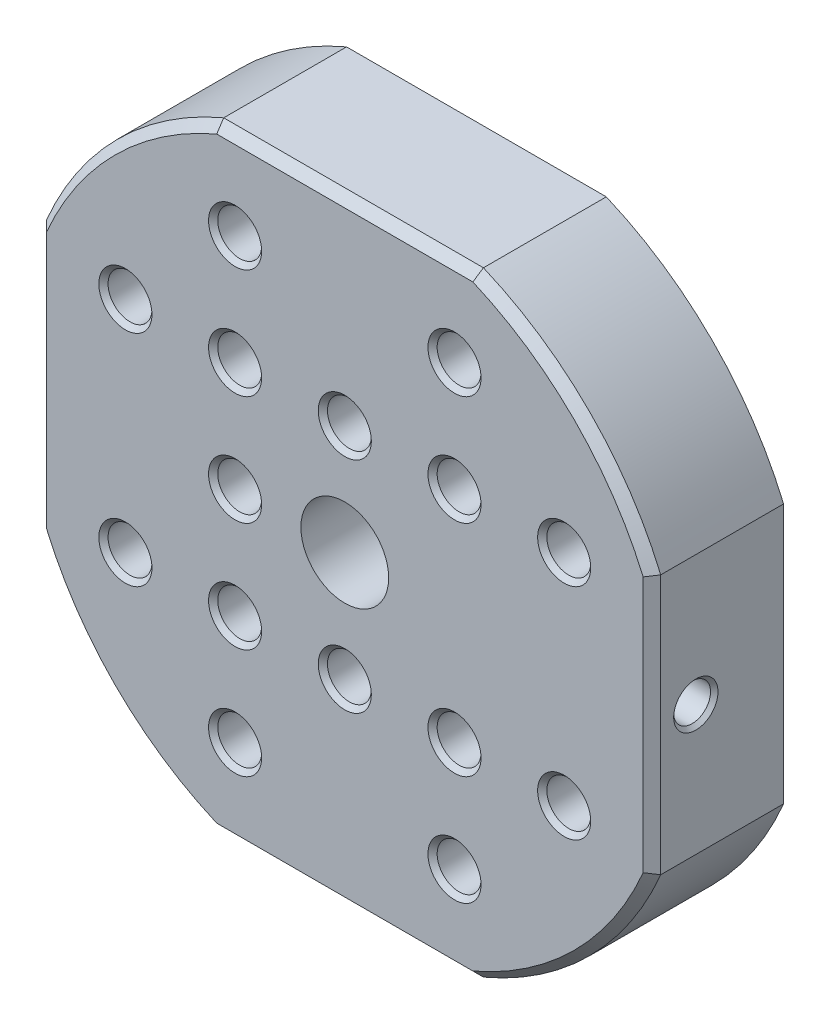
SolidWorks part; units mm, degrees
material "3.3547 (EN-AW 5083)"
ref_plane "Ebene vorne" through (0, 0, 0) normal (0, 0, 1) x (1, 0, 0)
ref_plane "Ebene oben" through (0, 0, 0) normal (0, 1, 0) x (1, 0, 0)
ref_plane "Ebene rechts" through (0, 0, 0) normal (1, 0, 0) x (0, 0, -1)
sketch "Skizze1" plane through (0, 0, 0) normal (0, 0, 1) x (1, 0, 0)
  line L1 (-36.9105, 30.5035) -> (29.0895, 30.5035)
  line L2 (-38.9105, 28.5035) -> (-38.9105, -37.4965)
  line L3 (-36.9105, -39.4965) -> (29.0895, -39.4965)
  line L4 (31.0895, 28.5035) -> (31.0895, -37.4965)
  arc A0 (-38.9105, -37.4965) -> (-36.9105, -39.4965) centre (-36.9105, -37.4965) ccw
  arc A1 (29.0895, -39.4965) -> (31.0895, -37.4965) centre (29.0895, -37.4965) ccw
  arc A2 (29.0895, 30.5035) -> (31.0895, 28.5035) centre (29.0895, 28.5035) cw
  arc A3 (-36.9105, 30.5035) -> (-38.9105, 28.5035) centre (-36.9105, 28.5035) ccw
  circle A4 centre (-3.9105, -4.4965) radius 5
  point P6 (-38.9105, -39.4965)
  point P11 (31.0895, 30.5035)
  point P14 (-38.9105, 30.5035)
  dimension "D3" = 2
  dimension "D1" = 70
  dimension "D2" = 70
extrude "Aufsatz-Linear austragen1" add sketch "Skizze1" along normal blind 15
sketch "Skizze4" plane through (0, 0, 0) normal (0, 0, -1) x (-1, 0, 0)
  circle A0 centre (3.9105, -4.4965) radius 24.75
extrude "Aufsatz-Linear austragen2" add sketch "Skizze4" along normal blind 3
sketch "Skizze2" plane through (0, 0, 15) normal (0, 0, 1) x (1, 0, 0)
  circle A1 centre (-16.4105, 20.5035) radius 2.5
  circle A3 centre (8.5895, 20.5035) radius 2.5
  circle A5 centre (-16.4105, 8.0035) radius 2.5
  circle A6 centre (-3.9105, 8.0035) radius 2.5
  circle A7 centre (8.5895, 8.0035) radius 2.5
  circle A8 centre (21.0895, 8.0035) radius 2.5
  circle A9 centre (-16.4105, -4.4965) radius 2.5
  circle A13 centre (-16.4105, -16.9965) radius 2.5
  circle A14 centre (-3.9105, -16.9965) radius 2.5
  circle A15 centre (8.5895, -16.9965) radius 2.5
  circle A16 centre (21.0895, -16.9965) radius 2.5
  circle A17 centre (-16.4105, -29.4965) radius 2.5
  circle A19 centre (8.5895, -29.4965) radius 2.5
  circle A21 centre (-28.9105, 8.0035) radius 2.5
  circle A23 centre (-28.9105, -16.9965) radius 2.5
extrude "Schnitt-Linear austragen1" cut sketch "Skizze2" against normal blind 20
cosmetic thread "Bohrungsgewinde1" parameters "D1"=13.95, "D2"=6
cosmetic thread "Bohrungsgewinde4" parameters "D1"=13.95, "D2"=6
cosmetic thread "Bohrungsgewinde6" parameters "D1"=13.95, "D2"=6
cosmetic thread "Bohrungsgewinde8" parameters "D1"=13.95, "D2"=6
cosmetic thread "Bohrungsgewinde9" parameters "D1"=13.95, "D2"=6
cosmetic thread "Bohrungsgewinde10" parameters "D1"=13.95, "D2"=6
cosmetic thread "Bohrungsgewinde11" parameters "D1"=13.95, "D2"=6
cosmetic thread "Bohrungsgewinde12" parameters "D1"=13.95, "D2"=6
cosmetic thread "Bohrungsgewinde15" parameters "D1"=13.95, "D2"=6
cosmetic thread "Bohrungsgewinde17" parameters "D1"=13.95, "D2"=6
cosmetic thread "Bohrungsgewinde18" parameters "D1"=13.95, "D2"=6
cosmetic thread "Bohrungsgewinde19" parameters "D1"=13.95, "D2"=6
cosmetic thread "Bohrungsgewinde20" parameters "D1"=13.95, "D2"=6
cosmetic thread "Bohrungsgewinde21" parameters "D1"=13.95, "D2"=6
cosmetic thread "Bohrungsgewinde23" parameters "D1"=13.95, "D2"=6
cosmetic thread "Bohrungsgewinde25" parameters "D1"=13.95, "D2"=6
cosmetic thread "Bohrungsgewinde28" parameters "D1"=13.95, "D2"=6
cosmetic thread "Bohrungsgewinde30" parameters "D1"=13.95, "D2"=6
cosmetic thread "Bohrungsgewinde32" parameters "D1"=13.95, "D2"=6
cosmetic thread "Bohrungsgewinde33" parameters "D1"=13.95, "D2"=6
cosmetic thread "Bohrungsgewinde34" parameters "D1"=13.95, "D2"=6
cosmetic thread "Bohrungsgewinde35" parameters "D1"=13.95, "D2"=6
cosmetic thread "Bohrungsgewinde36" parameters "D1"=13.95, "D2"=6
cosmetic thread "Bohrungsgewinde39" parameters "D1"=13.95, "D2"=6
cosmetic thread "Bohrungsgewinde41" parameters "D1"=13.95, "D2"=6
cosmetic thread "Bohrungsgewinde42" parameters "D1"=13.95, "D2"=6
cosmetic thread "Bohrungsgewinde43" parameters "D1"=13.95, "D2"=6
cosmetic thread "Bohrungsgewinde44" parameters "D1"=13.95, "D2"=6
cosmetic thread "Bohrungsgewinde45" parameters "D1"=13.95, "D2"=6
cosmetic thread "Bohrungsgewinde47" parameters "D1"=13.95, "D2"=6
cosmetic thread "Bohrungsgewinde49" parameters "D1"=13.95, "D2"=6
cosmetic thread "Bohrungsgewinde52" parameters "D1"=12.475, "D2"=6
cosmetic thread "Bohrungsgewinde54" parameters "D1"=12.475, "D2"=6
cosmetic thread "Bohrungsgewinde56" parameters "D1"=12.475, "D2"=6
cosmetic thread "Bohrungsgewinde57" parameters "D1"=12.475, "D2"=6
cosmetic thread "Bohrungsgewinde58" parameters "D1"=12.475, "D2"=6
cosmetic thread "Bohrungsgewinde59" parameters "D1"=12.475, "D2"=6
cosmetic thread "Bohrungsgewinde60" parameters "D1"=12.475, "D2"=6
cosmetic thread "Bohrungsgewinde63" parameters "D1"=12.475, "D2"=6
cosmetic thread "Bohrungsgewinde65" parameters "D1"=12.475, "D2"=6
cosmetic thread "Bohrungsgewinde66" parameters "D1"=12.475, "D2"=6
cosmetic thread "Bohrungsgewinde67" parameters "D1"=12.475, "D2"=6
cosmetic thread "Bohrungsgewinde68" parameters "D1"=12.475, "D2"=6
cosmetic thread "Bohrungsgewinde69" parameters "D1"=12.475, "D2"=6
cosmetic thread "Bohrungsgewinde71" parameters "D1"=12.475, "D2"=6
cosmetic thread "Bohrungsgewinde73" parameters "D1"=12.475, "D2"=6
hole_wizard "M6 Gewindebohrung1" positions "3D-Skizze1" profile "Skizze3" tap size "M6" standard "DIN"
sketch3d "3D-Skizze1"
  line L1 (-16.4105, 20.5035, 0) -> (-16.4105, 20.5035, 15) construction
  line L3 (8.5895, 20.5035, 0) -> (8.5895, 20.5035, 15) construction
  line L5 (21.0895, 8.0035, 0) -> (21.0895, 8.0035, 15) construction
  line L6 (8.5895, 8.0035, -3) -> (8.5895, 8.0035, 15) construction
  line L7 (-3.9105, 8.0035, -3) -> (-3.9105, 8.0035, 15) construction
  line L8 (-16.4105, 8.0035, -3) -> (-16.4105, 8.0035, 15) construction
  line L9 (-28.9105, 8.0035, 0) -> (-28.9105, 8.0035, 15) construction
  line L11 (-16.4105, -4.4965, -3) -> (-16.4105, -4.4965, 15) construction
  line L14 (21.0895, -16.9965, 0) -> (21.0895, -16.9965, 15) construction
  line L15 (8.5895, -16.9965, -3) -> (8.5895, -16.9965, 15) construction
  line L16 (-3.9105, -16.9965, -3) -> (-3.9105, -16.9965, 15) construction
  line L17 (-16.4105, -16.9965, -3) -> (-16.4105, -16.9965, 15) construction
  line L18 (-28.9105, -16.9965, 0) -> (-28.9105, -16.9965, 15) construction
  line L20 (-16.4105, -29.4965, 0) -> (-16.4105, -29.4965, 15) construction
  line L22 (8.5895, -29.4965, 0) -> (8.5895, -29.4965, 15) construction
  point P4 (-16.4105, 20.5035, 15)
  point P13 (8.5895, 20.5035, 15)
  point P21 (21.0895, 8.0035, 15)
  point P25 (8.5895, 8.0035, 15)
  point P29 (-3.9105, 8.0035, 15)
  point P33 (-16.4105, 8.0035, 15)
  point P37 (-28.9105, 8.0035, 15)
  point P45 (-16.4105, -4.4965, 15)
  point P57 (21.0895, -16.9965, 15)
  point P61 (8.5895, -16.9965, 15)
  point P65 (-3.9105, -16.9965, 15)
  point P69 (-16.4105, -16.9965, 15)
  point P73 (-28.9105, -16.9965, 15)
  point P81 (-16.4105, -29.4965, 15)
  point P89 (8.5895, -29.4965, 15)
sketch "Skizze3" plane through (-16.4105, 20.5035, 15) normal (1, 0, 0) x (0, -1, 0)
  line L0 (0, 0) -> (0, 11.5022)
  line L1 (0, 11.5022) -> (2.5, 10)
  line L2 (2.5, 10) -> (2.5, 0.525)
  line L3 (2.5, 0.525) -> (3.025, 0)
  line L5 (3.025, 0) -> (0, 0)
  line L6 (-2.5, 0.525) -> (-3.025, 0) construction
  line L10 (0, 11.5022) -> (-2.5, 10) construction
  line L11 (0, -6.35) -> (0, 107.95) construction
  dimension "Bohrerdurchmesser" = 5
  dimension "Bohrungstiefe" = 10
  dimension "Senkdurchmesser (Oben)" = 6.05
  dimension "Senkwinkel (Oben)" = 90
  dimension "Spitzenwinkel" = 118
cosmetic thread "Bohrungsgewinde75" parameters "D1"=0, "D2"=6
cosmetic thread "Bohrungsgewinde76" parameters "D1"=0, "D2"=6
cosmetic thread "Bohrungsgewinde77" parameters "D1"=0, "D2"=6
cosmetic thread "Bohrungsgewinde78" parameters "D1"=0, "D2"=6
cosmetic thread "Bohrungsgewinde79" parameters "D1"=0, "D2"=6
cosmetic thread "Bohrungsgewinde80" parameters "D1"=0, "D2"=6
cosmetic thread "Bohrungsgewinde81" parameters "D1"=0, "D2"=6
cosmetic thread "Bohrungsgewinde82" parameters "D1"=0, "D2"=6
sketch "Skizze5" plane through (0, 0, 0) normal (0, 0, 1) x (1, 0, 0)
  circle A0 centre (-3.9105, -4.4965) radius 5
extrude "Schnitt-Linear austragen2" cut sketch "Skizze5" against normal blind 13.25
sketch "Skizze6" plane through (0, 0, 15) normal (0, 0, 1) x (1, 0, 0)
  circle A0 centre (-3.9105, -4.4965) radius 38
  circle A1 centre (-3.9105, -4.4965) radius 60.6315
extrude "Schnitt-Linear austragen3" cut sketch "Skizze6" against normal blind 17
chamfer "Fase1" distance 1 angle 45 8 edges at (-3.9105, 30.5035, 15) (22.9596, 22.3735, 15) (31.0895, -4.4965, 15) (22.9596, -31.3666, 15) (-3.9105, -39.4965, 15) (-30.7805, -31.3666, 15) (-38.9105, -4.4965, 15) (-30.7805, 22.3735, 15)
sketch "Skizze7" plane through (31.0895, 0, 0) normal (1, 0, 0) x (0, 0, -1)
  line L0 (-15, -19.091) -> (-15, 10.098) construction
  circle A0 centre (-10, -4.4965) radius 2
  dimension "D1" = 5
extrude "Schnitt-Linear austragen4" cut sketch "Skizze7" against normal blind 38
hole_wizard "M5 Gewindebohrung1" positions "3D-Skizze2" profile "Skizze8" tap size "M5" standard "DIN"
sketch3d "3D-Skizze2"
  line L0 (0.6721, -4.4965, 10) -> (31.0895, -4.4965, 10) construction
  point P0 (31.0895, -4.4965, 10)
cosmetic thread "Bohrungsgewinde83" parameters "D1"=10, "D2"=5
sketch "Skizze8" plane through (31.0895, -4.4965, 10) normal (0, 1, 0) x (0, 0, -1)
  line L0 (0, 0) -> (0, 35.2618)
  line L1 (0, 35.2618) -> (2.1, 34)
  line L2 (2.1, 34) -> (2.1, 0.425)
  line L3 (2.1, 0.425) -> (2.525, 0)
  line L5 (2.525, 0) -> (0, 0)
  line L6 (-2.1, 0.425) -> (-2.525, 0) construction
  line L10 (0, 35.2618) -> (-2.1, 34) construction
  line L11 (0, -6.35) -> (0, 107.95) construction
  dimension "Bohrerdurchmesser" = 4.2
  dimension "Bohrungstiefe" = 34
  dimension "Senkdurchmesser (Oben)" = 5.05
  dimension "Senkwinkel (Oben)" = 90
  dimension "Spitzenwinkel" = 118
sketch "Skizze10" plane through (0, 0, -3) normal (0, 0, -1) x (-1, 0, 0)
  circle A0 centre (3.9105, -4.4965) radius 15.05
extrude "Schnitt-Linear austragen5" cut sketch "Skizze10" against normal blind 0.5
sketch "Skizze11" plane through (0, 0, 15) normal (0, 0, 1) x (1, 0, 0)
  circle A0 centre (-3.9105, -4.4965) radius 38
